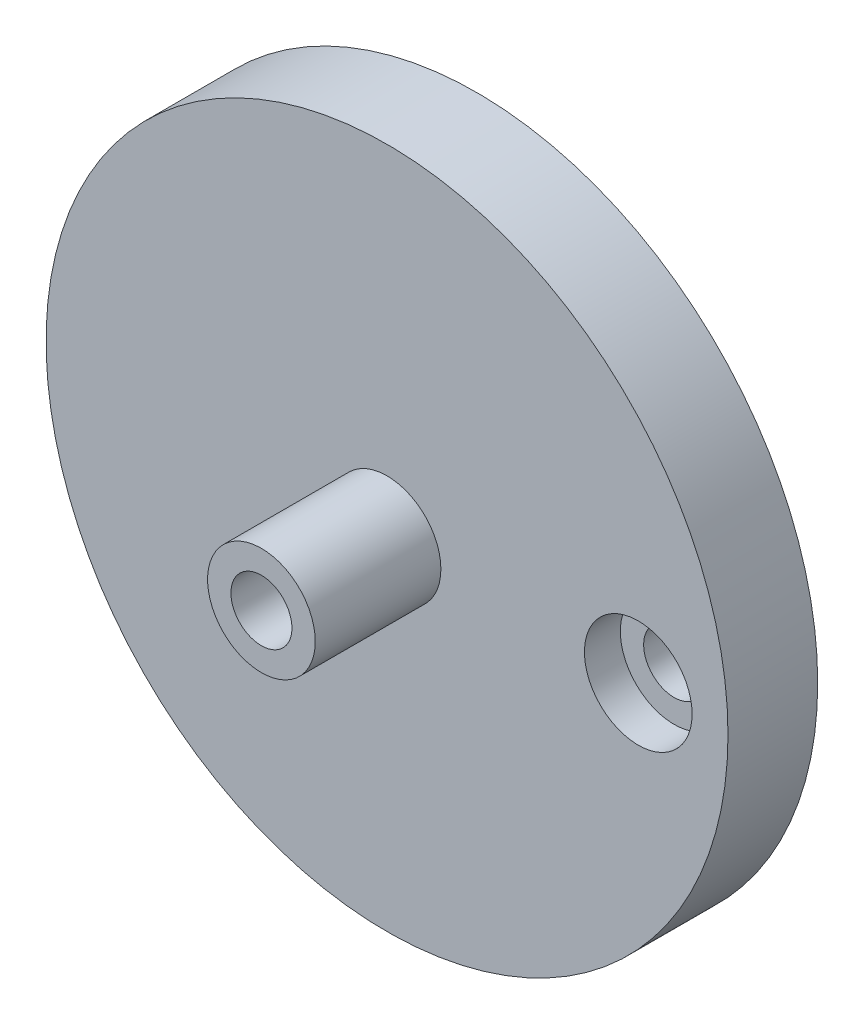
SolidWorks part; units mm, degrees
ref_plane "Front Plane" through (0, 0, 0) normal (1, 0, 0) x (0, 1, 0)
ref_plane "Top Plane" through (0, 0, 0) normal (0, 0, 1) x (0, 1, 0)
ref_plane "Right Plane" through (0, 0, 0) normal (0, 1, 0) x (-1, 0, 0)
sketch "Sketch1" plane through (0, 0, 0) normal (0, 0, 1) x (0, 1, 0)
  circle A0 centre (0, 0) radius 19
  dimension "D1" = 38
extrude "Boss-Extrude1" add sketch "Sketch1" along normal blind 5 contours A0
sketch "Sketch2" plane through (0, 0, 5) normal (0, 0, 1) x (1, 0, 0)
  circle A0 centre (0, 0) radius 3
  dimension "D1" = 6
extrude "Boss-Extrude2" add sketch "Sketch2" along normal blind 7
sketch "Sketch3" plane through (0, 0, 12) normal (0, 0, 1) x (1, 0, 0)
  circle A0 centre (0, 0) radius 1.7
  dimension "D1" = 3.4
extrude "Cut-Extrude1" cut sketch "Sketch3" against normal through all
sketch "Sketch4" plane through (0, 0, 0) normal (0, 0, -1) x (1, 0, 0)
  circle A0 centre (0, 0) radius 3
  dimension "D1" = 6
extrude "Cut-Extrude2" cut sketch "Sketch4" against normal blind 2
sketch "Sketch5" plane through (0, 0, 0) normal (0, 0, -1) x (1, 0, 0)
  circle A0 centre (14, 0) radius 1.7
  dimension "D2" = 3.4
  dimension "D1" = 14
extrude "Cut-Extrude3" cut sketch "Sketch5" against normal through all and the other way through all
sketch "Sketch6" plane through (0, 0, 5) normal (0, 0, 1) x (1, 0, 0)
  circle A0 centre (14, 0) radius 3
  dimension "D1" = 6
extrude "Cut-Extrude4" cut sketch "Sketch6" against normal blind 2
